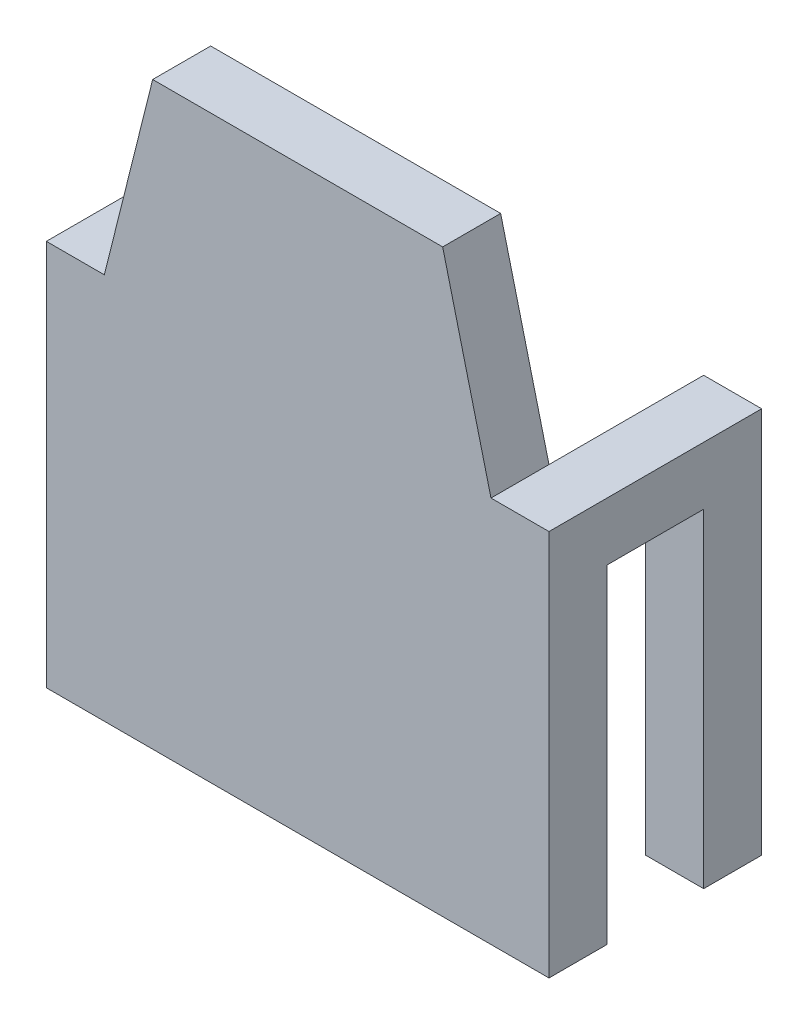
SolidWorks part; units mm, degrees
ref_plane "前视基准面" through (0, 0, 0) normal (0, 0, 1) x (1, 0, 0)
ref_plane "上视基准面" through (0, 0, 0) normal (0, 1, 0) x (1, 0, 0)
ref_plane "右视基准面" through (0, 0, 0) normal (1, 0, 0) x (0, 0, -1)
sketch "草图1" plane through (0, 0, 0) normal (0, 0, 1) x (1, 0, 0)
  line L0 (2.5, 0) -> (0, -10)
  line L1 (2.5, 0) -> (17.5, 0)
  line L3 (0, -30) -> (20, -30)
  line L5 (17.5, 0) -> (20, -10)
  line L6 (0, -10) -> (-3, -10)
  line L7 (-3, -10) -> (-3, -30)
  line L8 (-3, -30) -> (0, -30)
  line L9 (20, -10) -> (23, -10)
  line L10 (23, -10) -> (23, -30)
  line L11 (23, -30) -> (20, -30)
  dimension "D2" = 10
  dimension "D4" = 10
  dimension "D5" = 20
  dimension "D6" = 30
  dimension "D7" = 3
  dimension "D8" = 3
extrude "凸台-拉伸1" add sketch "草图1" along normal blind 3
sketch "草图4" plane through (0, 0, 0) normal (0, 0, -1) x (-1, 0, 0)
  line L1 (-23, -10) -> (-20, -10)
  line L2 (-23, -10) -> (-23, -13)
  line L3 (-23, -13) -> (-20, -13)
  line L4 (-20, -10) -> (-20, -13)
  line L5 (3, -10) -> (0, -10)
  line L6 (3, -10) -> (3, -13)
  line L7 (3, -13) -> (0, -13)
  line L8 (0, -10) -> (0, -13)
  dimension "D1" = 3
  dimension "D2" = 3
  dimension "D3" = 3
  dimension "D4" = 3
extrude "凸台-拉伸2" add sketch "草图4" along normal blind 8
sketch "草图5" plane through (0, -13, 0) normal (0, -1, 0) x (1, 0, 0)
  line L1 (-3, -8) -> (0, -8)
  line L2 (-3, -8) -> (-3, -5)
  line L3 (-3, -5) -> (0, -5)
  line L4 (0, -8) -> (0, -5)
  line L6 (20, -8) -> (23, -8)
  line L7 (20, -8) -> (20, -5)
  line L8 (20, -5) -> (23, -5)
  line L9 (23, -8) -> (23, -5)
  line L10 (0, -8) -> (-3, -8) construction
  line L11 (23, -8) -> (20, -8) construction
  dimension "D1" = 3
  dimension "D2" = 3
  dimension "D3" = 3
  dimension "D4" = 3
extrude "凸台-拉伸3" add sketch "草图5" along normal up to surface (17 mm away) up to face at (10, -30, 1.5)
sketch "草图6" plane through (0, 0, 0) normal (0, 0, -1) x (-1, 0, 0)
  line L0 (-20, -10) -> (0, -30) construction
  line L1 (0, -10) -> (-20, -30) construction
  circle A0 centre (-10, -20) radius 5
  dimension "D1" = 10
extrude "切除-拉伸1" cut sketch "草图6" against normal blind 2
